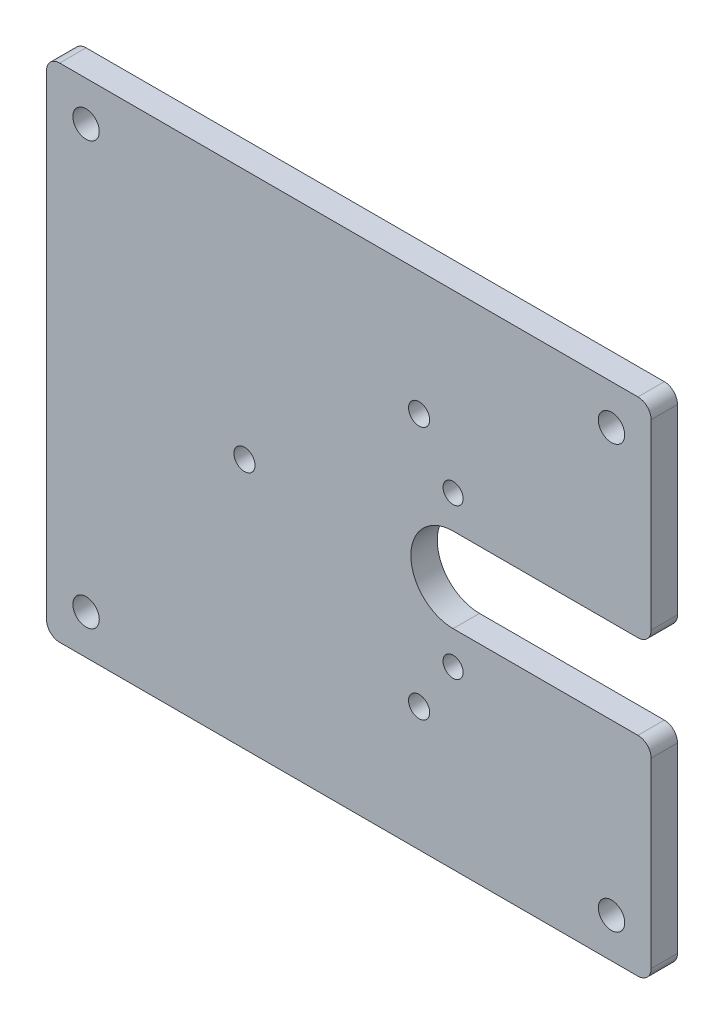
SolidWorks part; units mm, degrees
ref_plane "Front Plane" through (0, 0, 0) normal (0, 0, 1) x (1, 0, 0)
ref_plane "Top Plane" through (0, 0, 0) normal (0, 1, 0) x (1, 0, 0)
ref_plane "Right Plane" through (0, 0, 0) normal (1, 0, 0) x (0, 0, -1)
sketch "Sketch1" plane through (0, 0, 0) normal (0, 0, 1) x (1, 0, 0)
  line L0 (-17.5, 0) -> (51.6073, 0) construction
  line L1 (-17.5, 0) -> (-87.3001, 0) construction
  line L2 (-55, 45) -> (-55, -45)
  line L3 (-52.5, -47.5) -> (57, -47.5)
  line L4 (59.5, -45) -> (59.5, -10.5)
  line L5 (22, -14.25) -> (22, 0) construction
  line L6 (22, -8) -> (57, -8)
  line L7 (22, 8) -> (57, 8)
  line L8 (59.5, 45) -> (59.5, 10.5)
  line L9 (-52.5, 47.5) -> (57, 47.5)
  circle A0 centre (15.5628, 24) radius 2
  circle A1 centre (22, -14.25) radius 1.9
  circle A2 centre (22, 14.25) radius 1.9
  circle A4 centre (52, -40) radius 2.5
  circle A6 centre (-47.5, -40) radius 2.5
  circle A7 centre (15.5628, -24) radius 2
  arc A8 (22, 8) -> (22, -8) centre (22, 0) ccw
  arc A10 (57, -8) -> (59.5, -10.5) centre (57, -10.5) cw
  circle A11 centre (-17.5, 0) radius 2
  arc A12 (57, -47.5) -> (59.5, -45) centre (57, -45) ccw
  arc A13 (-52.5, -47.5) -> (-55, -45) centre (-52.5, -45) cw
  arc A14 (57, 8) -> (59.5, 10.5) centre (57, 10.5) ccw
  arc A15 (57, 47.5) -> (59.5, 45) centre (57, 45) cw
  arc A16 (-52.5, 47.5) -> (-55, 45) centre (-52.5, 45) ccw
  circle A17 centre (-47.5, 40) radius 2.5
  circle A18 centre (52, 40) radius 2.5
  dimension "D4" = 4
  dimension "D5" = 3.8
  dimension "D6" = 4
  dimension "D12" = 5
  dimension "D15" = 5
  dimension "D18" = 16
  dimension "D10" = 2.5
  dimension "D19" = 2.5
  dimension "D20" = 2.5
  dimension "D1" = 28.5
  dimension "D2" = 24
  dimension "D3" = 17.5
  dimension "D7" = 11.6833
  dimension "D8" = 41.9918
  dimension "D9" = 30
  dimension "D11" = 30
  dimension "D13" = 7.5
  dimension "D14" = 7.5
  dimension "D16" = 7.5
  dimension "D17" = 7.5
  dimension "D21" = 80
extrude "Boss-Extrude1" add sketch "Sketch1" along normal blind 5
